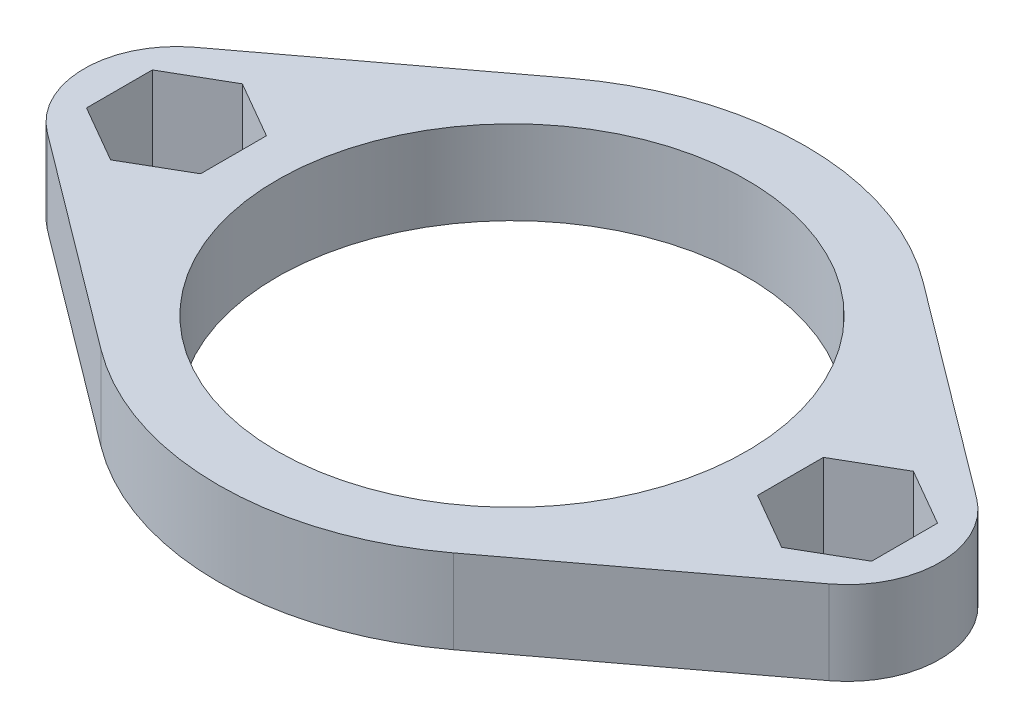
SolidWorks part; units mm, degrees
material "Delrin 2700 NC010, Low Viscosity Acetal Copolymer (SS)"
ref_plane "Front Plane" through (0, 0, 0) normal (0, 0, 1) x (1, 0, 0)
ref_plane "Top Plane" through (0, 0, 0) normal (0, 1, 0) x (1, 0, 0)
ref_plane "Right Plane" through (0, 0, 0) normal (1, 0, 0) x (0, 0, -1)
sketch "Sketch1" plane through (0, 0, 0) normal (0, 1, 0) x (1, 0, 0)
  line L0 (0, 0) -> (0, -27.5855) construction
  line L1 (-8.5, 0) -> (8.5, 0) construction
  line L2 (-23.3, 4.4) -> (-10.5, 14)
  line L3 (-23.3, -4.4) -> (-10.5, -14)
  line L4 (23.3, -4.4) -> (10.5, -14)
  line L5 (23.3, 4.4) -> (10.5, 14)
  line L7 (-20, 3.926) -> (-23.4, 1.963)
  line L8 (-23.4, 1.963) -> (-23.4, -1.963)
  line L9 (-23.4, -1.963) -> (-20, -3.926)
  line L10 (-20, -3.926) -> (-16.6, -1.963)
  line L11 (-16.6, -1.963) -> (-16.6, 1.963)
  line L12 (-16.6, 1.963) -> (-20, 3.926)
  line L13 (20, -3.926) -> (23.4, -1.963)
  line L14 (23.4, -1.963) -> (23.4, 1.963)
  line L15 (23.4, 1.963) -> (20, 3.926)
  line L16 (20, 3.926) -> (16.6, 1.963)
  line L17 (16.6, 1.963) -> (16.6, -1.963)
  line L18 (16.6, -1.963) -> (20, -3.926)
  arc A0 (-10.5, -14) -> (10.5, -14) centre (0, 0) ccw
  circle A1 centre (-20, 0) radius 2 construction
  circle A2 centre (-20, 0) radius 3.4 construction
  arc A3 (-23.3, 4.4) -> (-23.3, -4.4) centre (-20, 0) ccw
  circle A4 centre (20, 0) radius 3.4 construction
  circle A5 centre (20, 0) radius 2 construction
  arc A6 (23.3, 4.4) -> (23.3, -4.4) centre (20, 0) cw
  arc A7 (10.5, 14) -> (-10.5, 14) centre (0, 0) ccw
  circle A8 centre (0, 0) radius 14
  dimension "D1" = 17
  dimension "D2" = 35
  dimension "D3" = 6.8
  dimension "D4" = 4
  dimension "D6" = 11
  dimension "D7" = 28
  dimension "D5" = 40
extrude "Boss-Extrude1" add sketch "Sketch1" along normal blind 5
